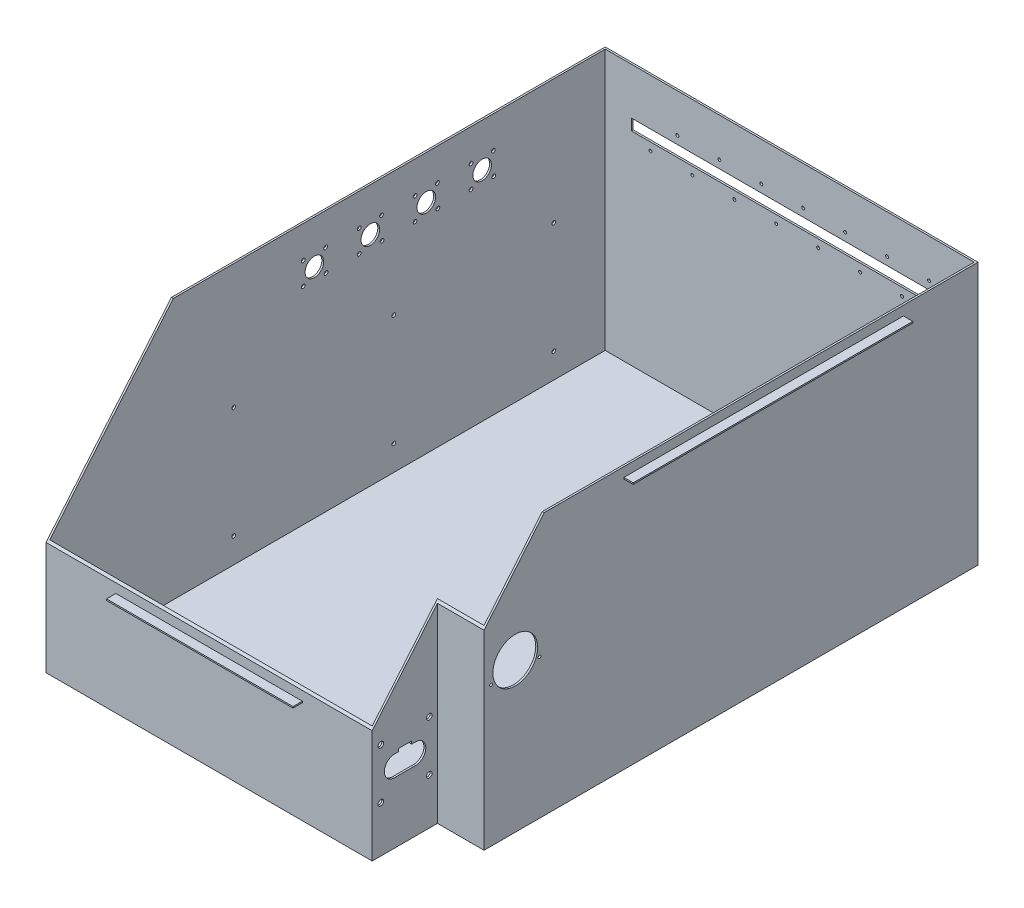
SolidWorks part; units mm, degrees
ref_plane "Front Plane" through (0, 0, 0) normal (0, 0, 1) x (1, 0, 0)
ref_plane "Top Plane" through (0, 0, 0) normal (0, 1, 0) x (1, 0, 0)
ref_plane "Right Plane" through (0, 0, 0) normal (1, 0, 0) x (0, 0, -1)
sketch "Sketch1" plane through (0, 0, 0) normal (0, 1, 0) x (1, 0, 0)
  line L1 (-200, 237.8263) -> (200, 237.8263)
  line L2 (-200, 237.8263) -> (-200, -362.1737)
  line L3 (-200, -362.1737) -> (150, -362.1737)
  line L4 (200, 237.8263) -> (200, -292.1737)
  line L6 (200, -292.1737) -> (150, -292.1737)
  line L7 (150, -292.1737) -> (150, -362.1737)
  line L8 (0, -55) -> (0, 55) construction
  point P1 (0, 237.8263)
  dimension "D1" = 600
  dimension "D2" = 400
  dimension "D5" = 70
  dimension "D6" = 50
extrude "Boss-Extrude1" add sketch "Sketch1" along normal blind 1.5
sketch "Sketch2" plane through (0, 1.5, 0) normal (0, 1, 0) x (1, 0, 0)
  line L60 (-198, 235.8263) -> (-198, -360.1737)
  line L61 (-198, -360.1737) -> (148, -360.1737)
  line L62 (148, -360.1737) -> (148, -290.1737)
  line L63 (148, -290.1737) -> (198, -290.1737)
  line L64 (198, -290.1737) -> (198, 235.8263)
  line L65 (198, 235.8263) -> (-198, 235.8263)
  line L66 (-200, 237.8263) -> (-200, -362.1737)
  line L67 (-200, -362.1737) -> (150, -362.1737)
  line L68 (150, -362.1737) -> (150, -292.1737)
  line L69 (150, -292.1737) -> (200, -292.1737)
  line L70 (200, -292.1737) -> (200, 237.8263)
  line L71 (200, 237.8263) -> (-200, 237.8263)
  line L72 (-200, 237.8263) -> (-200, -362.1737)
  line L73 (-200, -362.1737) -> (150, -362.1737)
  line L74 (150, -362.1737) -> (150, -292.1737)
  line L75 (150, -292.1737) -> (200, -292.1737)
  line L76 (200, -292.1737) -> (200, 237.8263)
  line L77 (200, 237.8263) -> (-200, 237.8263)
  dimension "D3" = 2
  dimension "D4" = 2
  dimension "D2" = 2
  dimension "D5" = 2
  dimension "D6" = 2
  dimension "D1" = 0
extrude "Boss-Extrude2" add sketch "Sketch2" along normal blind 280
sketch "Sketch3" plane through (-200, 0, 0) normal (-1, 0, 0) x (0, 0, 1)
  line L3 (362.1737, 281.5) -> (362.1737, 0) construction
  line L4 (362.1737, 121.1176) -> (227.5969, 281.5)
  line L6 (-237.8263, 281.5) -> (362.1737, 281.5) construction
  line L9 (362.1737, 281.5) -> (362.1737, 121.1176)
  line L10 (227.5969, 281.5) -> (362.1737, 281.5)
  dimension "D1" = 50
sketch "Sketch4" plane through (0, 0, -237.8263) normal (0, 0, -1) x (-1, 0, 0)
  line L0 (-200, 281.5) -> (-200, 0) construction
  line L1 (-200, 234.6761) -> (200, 234.6761)
  line L2 (-200, 234.6761) -> (-200, 192.2905)
  line L3 (-200, 192.2905) -> (200, 192.2905)
  line L4 (200, 234.6761) -> (200, 192.2905)
  line L5 (200, 281.5) -> (200, 0) construction
extrude "Boss-Extrude3" add sketch "Sketch4" against normal blind 2
extrude "Cut-Extrude1" cut sketch "Sketch3" against normal through all both and the other way through all
sketch "Sketch5" plane through (-200, 0, 0) normal (-1, 0, 0) x (0, 0, 1)
  line L0 (-115.8263, 223.1206) -> (-115.8263, 247.1206) construction
  line L5 (-115.8263, 223.1206) -> (-91.8263, 223.1206) construction
  line L6 (-115.8263, 247.1206) -> (-91.8263, 247.1206) construction
  line L7 (-91.8263, 223.1206) -> (-91.8263, 247.1206) construction
  line L8 (-115.8263, 223.1206) -> (-91.8263, 247.1206) construction
  line L9 (-115.8263, 247.1206) -> (-91.8263, 223.1206) construction
  line L10 (-55.8263, 223.1206) -> (-55.8263, 247.1206) construction
  line L11 (-55.8263, 223.1206) -> (-31.8263, 223.1206) construction
  line L12 (-55.8263, 247.1206) -> (-31.8263, 247.1206) construction
  line L13 (-31.8263, 223.1206) -> (-31.8263, 247.1206) construction
  line L14 (-55.8263, 223.1206) -> (-31.8263, 247.1206) construction
  line L15 (-55.8263, 247.1206) -> (-31.8263, 223.1206) construction
  line L16 (4.1737, 223.1206) -> (4.1737, 247.1206) construction
  line L17 (4.1737, 223.1206) -> (28.1737, 223.1206) construction
  line L18 (4.1737, 247.1206) -> (28.1737, 247.1206) construction
  line L19 (28.1737, 223.1206) -> (28.1737, 247.1206) construction
  line L20 (4.1737, 223.1206) -> (28.1737, 247.1206) construction
  line L21 (4.1737, 247.1206) -> (28.1737, 223.1206) construction
  line L22 (64.1737, 223.1206) -> (64.1737, 247.1206) construction
  line L23 (64.1737, 223.1206) -> (88.1737, 223.1206) construction
  line L24 (64.1737, 247.1206) -> (88.1737, 247.1206) construction
  line L25 (88.1737, 223.1206) -> (88.1737, 247.1206) construction
  line L26 (64.1737, 223.1206) -> (88.1737, 247.1206) construction
  line L27 (64.1737, 247.1206) -> (88.1737, 223.1206) construction
  line L28 (-235.8263, 281.5) -> (-235.8263, 1.5) construction
  circle A0 centre (-115.8263, 247.1206) radius 2
  circle A1 centre (-116.3263, 223.1259) radius 2
  circle A2 centre (-91.8263, 223.1206) radius 2
  circle A3 centre (-91.8263, 247.1206) radius 2
  circle A4 centre (-103.8263, 235.1206) radius 10
  circle A5 centre (-55.8263, 247.1206) radius 2
  circle A6 centre (-56.3263, 223.1259) radius 2
  circle A7 centre (-31.8263, 223.1206) radius 2
  circle A8 centre (-31.8263, 247.1206) radius 2
  circle A9 centre (-43.8263, 235.1206) radius 10
  circle A10 centre (4.1737, 247.1206) radius 2
  circle A11 centre (3.6737, 223.1259) radius 2
  circle A12 centre (28.1737, 223.1206) radius 2
  circle A13 centre (28.1737, 247.1206) radius 2
  circle A14 centre (16.1737, 235.1206) radius 10
  circle A15 centre (64.1737, 247.1206) radius 2
  circle A16 centre (63.6737, 223.1259) radius 2
  circle A17 centre (88.1737, 223.1206) radius 2
  circle A18 centre (88.1737, 247.1206) radius 2
  circle A19 centre (76.1737, 235.1206) radius 10
  point P9 (-103.8263, 235.1206)
  point P24 (-43.8263, 235.1206)
  point P38 (16.1737, 235.1206)
  point P52 (76.1737, 235.1206)
  dimension "D2" = 20
  dimension "D5" = 4
  dimension "D1" = 24
  dimension "D3" = 24
  dimension "D4" = 24
  dimension "D7" = 120
  dimension "D6" = 4
sketch "Sketch6" plane through (-198, 0, 0) normal (1, 0, 0) x (0, 0, -1)
  arc A0 (151.1392, 167.4539) -> (156.7272, 167.4539) centre (153.9332, 167.4539) ccw construction
  arc A1 (-68.8756, 167.4539) -> (-63.2876, 167.4539) centre (-66.0816, 167.4539) ccw construction
  arc A2 (-178.883, 167.4539) -> (-173.295, 167.4539) centre (-176.089, 167.4539) ccw construction
  arc A3 (151.1392, 167.4539) -> (156.7272, 167.4539) centre (153.9332, 167.4539) ccw
  arc A4 (-68.8756, 167.4539) -> (-63.2876, 167.4539) centre (-66.0816, 167.4539) ccw
  arc A5 (-178.883, 167.4539) -> (-173.295, 167.4539) centre (-176.089, 167.4539) ccw
  circle A6 centre (-176.089, 167.4539) radius 2.794
  circle A7 centre (-176.089, 167.4539) radius 4.5
  circle A8 centre (-64.4633, 167.4539) radius 4.5
  circle A9 centre (-64.4633, 167.4539) radius 2.794
  circle A10 centre (155.5515, 167.4539) radius 2.794
  circle A11 centre (155.5515, 167.4539) radius 4.5
  dimension "D1" = 9
extrude "Boss-Extrude4" [suppressed] add sketch "Sketch6" along normal blind 50 contours A4 A9 | A8 | A7 | A6 | A11 | A10
sketch "Sketch8" plane through (-198, 0, 0) normal (1, 0, 0) x (0, 0, -1)
  line L0 (235.8263, 1.5) -> (-360.1737, 1.5) construction
  line L1 (-360.1737, 123.5011) -> (-360.1737, 1.5) construction
  circle A0 centre (-265.6737, 172.1992) radius 2.39
  circle A1 centre (-265.6737, 172.1992) radius 4.39
  circle A2 centre (-265.1737, 16.5) radius 2.39
  circle A3 centre (-265.1737, 16.5) radius 4.39
  dimension "D3" = 4.78
  dimension "D4" = 2
  dimension "D1" = 155.7
  dimension "D2" = 15
  dimension "D5" = 95
extrude "Boss-Extrude5" [suppressed] add sketch "Sketch8" along normal blind 15
sketch "Sketch10" plane through (148, 0, 0) normal (-1, 0, 0) x (0, 0, 1)
  line L0 (315.6737, 86.5) -> (320.9237, 86.5) construction
  line L1 (315.6737, 66.5) -> (338.1737, 66.5) construction
  line L2 (338.1737, 76.5) -> (315.6737, 76.5) construction
  line L3 (360.1737, 1.5) -> (290.1737, 1.5) construction
  line L5 (320.9237, 86.5) -> (320.9237, 89.5) construction
  line L6 (320.9237, 89.5) -> (332.9237, 89.5) construction
  line L7 (332.9237, 86.5) -> (332.9237, 89.5) construction
  line L8 (360.1737, 123.5011) -> (360.1737, 1.5) construction
  line L9 (332.9237, 86.5) -> (338.1737, 86.5) construction
  line L10 (319.9237, 90.5) -> (333.9237, 90.5)
  line L11 (333.9237, 87.5) -> (333.9237, 90.5)
  line L12 (333.9237, 87.5) -> (338.1737, 87.5)
  line L13 (315.6737, 65.5) -> (338.1737, 65.5)
  line L14 (315.6737, 87.5) -> (319.9237, 87.5)
  line L15 (319.9237, 87.5) -> (319.9237, 90.5)
  line L17 (300.9737, 49.55) -> (352.8737, 49.55) construction
  line L18 (300.9737, 49.55) -> (300.9737, 103.45) construction
  line L19 (300.9737, 103.45) -> (352.8737, 103.45) construction
  line L20 (352.8737, 49.55) -> (352.8737, 103.45) construction
  line L21 (300.9737, 49.55) -> (352.8737, 103.45) construction
  line L22 (300.9737, 103.45) -> (352.8737, 49.55) construction
  arc A0 (315.6737, 86.5) -> (315.6737, 66.5) centre (315.6737, 76.5) ccw construction
  arc A1 (338.1737, 66.5) -> (338.1737, 86.5) centre (338.1737, 76.5) ccw construction
  arc A2 (338.1737, 65.5) -> (338.1737, 87.5) centre (338.1737, 76.5) ccw
  arc A3 (315.6737, 87.5) -> (315.6737, 65.5) centre (315.6737, 76.5) ccw
  circle A4 centre (300.9737, 103.45) radius 3
  circle A5 centre (352.8737, 103.45) radius 3
  circle A6 centre (300.9737, 49.55) radius 3
  circle A7 centre (352.8737, 49.55) radius 3
  point P12 (326.9237, 89.5)
  point P13 (326.9237, 76.5)
  point P26 (326.9237, 76.5)
  dimension "D1" = 65
  dimension "D2" = 22.5
  dimension "D6" = 20
  dimension "D10" = 6
  dimension "D3" = 22
  dimension "D4" = 12
  dimension "D5" = 3
  dimension "D8" = 51.9
  dimension "D9" = 53.9
  dimension "D7" = 1
extrude "Cut-Extrude2" cut sketch "Sketch10" against normal up to surface (2 mm away)
sketch "Sketch11" plane through (148, 0, 0) normal (-1, 0, 0) x (0, 0, 1)
  line L0 (298.4737, 103.43) -> (298.4737, 49.53) construction
  line L13 (315.6737, 66.5) -> (338.1737, 66.5) construction
  line L14 (315.6737, 86.5) -> (320.9237, 86.5) construction
  line L15 (315.6737, 66.5) -> (338.1737, 66.5)
  line L19 (315.6737, 86.5) -> (318.4237, 86.5)
  line L20 (333.9237, 90.5) -> (319.9237, 90.5)
  line L21 (333.9237, 90.5) -> (319.9237, 90.5)
  line L22 (333.9237, 87.5) -> (333.9237, 90.5)
  line L23 (333.9237, 87.5) -> (333.9237, 90.5)
  line L28 (330.4237, 86.5) -> (320.9237, 86.5)
  line L29 (315.7815, 66) -> (338.2021, 66)
  line L30 (330.9237, 86) -> (320.2852, 86)
  line L31 (330.9237, 86) -> (330.9237, 91)
  line L32 (330.9237, 91) -> (317.9237, 91)
  line L33 (317.9237, 91) -> (317.9237, 87)
  line L34 (315.7815, 87) -> (317.9237, 87)
  line L36 (298.4737, 103.43) -> (350.3737, 103.43) construction
  line L43 (333.9237, 90.5) -> (319.9237, 90.5)
  line L44 (333.9237, 90.5) -> (319.9237, 90.5)
  line L45 (333.9237, 87.5) -> (333.9237, 90.5)
  line L46 (333.9237, 87.5) -> (333.9237, 90.5)
  line L47 (338.1737, 87.5) -> (333.9237, 87.5)
  line L48 (338.1737, 87.5) -> (333.9237, 87.5)
  line L49 (315.6737, 65.5) -> (338.1737, 65.5)
  line L50 (315.6737, 65.5) -> (338.1737, 65.5)
  line L51 (319.9237, 87.5) -> (315.6737, 87.5)
  line L52 (319.9237, 87.5) -> (315.6737, 87.5)
  line L53 (319.9237, 90.5) -> (319.9237, 87.5)
  line L54 (319.9237, 90.5) -> (319.9237, 87.5)
  line L55 (333.9237, 90.5) -> (319.9237, 90.5)
  line L56 (333.9237, 90.5) -> (319.9237, 90.5)
  line L57 (333.9237, 87.5) -> (333.9237, 90.5)
  line L58 (333.9237, 87.5) -> (333.9237, 90.5)
  line L59 (338.1737, 87.5) -> (333.9237, 87.5)
  line L60 (338.1737, 87.5) -> (333.9237, 87.5)
  line L61 (315.6737, 65.5) -> (338.1737, 65.5)
  line L62 (315.6737, 65.5) -> (338.1737, 65.5)
  line L63 (319.9237, 87.5) -> (315.6737, 87.5)
  line L64 (319.9237, 87.5) -> (315.6737, 87.5)
  line L65 (319.9237, 90.5) -> (319.9237, 87.5)
  line L66 (319.9237, 90.5) -> (319.9237, 87.5)
  line L67 (330.4237, 86.5) -> (330.4237, 90.5) construction
  line L68 (330.4237, 90.5) -> (318.4237, 90.5) construction
  line L69 (318.4237, 90.5) -> (318.4237, 86.5) construction
  line L70 (338.1737, 87.5) -> (333.9237, 87.5)
  line L71 (338.1737, 87.5) -> (333.9237, 87.5)
  line L72 (315.6737, 65.5) -> (338.1737, 65.5)
  line L73 (315.6737, 65.5) -> (338.1737, 65.5)
  line L74 (319.9237, 87.5) -> (315.6737, 87.5)
  line L75 (319.9237, 87.5) -> (315.6737, 87.5)
  line L76 (319.9237, 90.5) -> (319.9237, 87.5)
  line L77 (319.9237, 90.5) -> (319.9237, 87.5)
  arc A4 (338.2021, 66) -> (320.2852, 86) centre (336.3485, 82.3648) ccw
  arc A5 (338.1737, 65.5) -> (338.1737, 87.5) centre (338.1737, 76.5) ccw
  arc A7 (338.1737, 65.5) -> (338.1737, 87.5) centre (338.1737, 76.5) ccw
  arc A9 (315.7815, 87) -> (315.7815, 66) centre (311.0911, 76.5) ccw
  circle A10 centre (298.4737, 103.43) radius 3
  circle A11 centre (298.4737, 49.53) radius 3
  circle A12 centre (350.3737, 103.43) radius 3
  circle A13 centre (350.3737, 49.53) radius 3
  arc A16 (338.1737, 66.5) -> (320.9237, 86.5) centre (336.3485, 82.3648) ccw construction
  arc A17 (338.1737, 65.5) -> (338.1737, 87.5) centre (338.1737, 76.5) ccw
  arc A18 (315.6737, 87.5) -> (315.6737, 65.5) centre (315.6737, 76.5) ccw
  arc A19 (315.6737, 87.5) -> (315.6737, 65.5) centre (315.6737, 76.5) ccw
  arc A20 (315.6737, 86.5) -> (315.6737, 66.5) centre (311.0911, 76.5) ccw construction
  arc A21 (338.1737, 65.5) -> (338.1737, 87.5) centre (338.1737, 76.5) ccw
  arc A22 (315.6737, 87.5) -> (315.6737, 65.5) centre (315.6737, 76.5) ccw
  arc A23 (315.6737, 87.5) -> (315.6737, 65.5) centre (315.6737, 76.5) ccw
  arc A24 (338.1737, 65.5) -> (338.1737, 87.5) centre (338.1737, 76.5) ccw
  arc A25 (338.1737, 65.5) -> (338.1737, 87.5) centre (338.1737, 76.5) ccw
  arc A26 (315.6737, 87.5) -> (315.6737, 65.5) centre (315.6737, 76.5) ccw
  arc A27 (315.6737, 87.5) -> (315.6737, 65.5) centre (315.6737, 76.5) ccw
  dimension "D5" = 6
  dimension "D6" = 51.9
  dimension "D7" = 53.9
  dimension "D1" = 0
  dimension "D2" = 0
  dimension "D3" = 0
  dimension "D4" = 0.5
extrude "Cut-Extrude3" [suppressed] cut sketch "Sketch11" against normal through all
sketch "Sketch14" plane through (148, 0, 0) normal (-1, 0, 0) x (0, 0, 1)
  line L0 (362.1737, 121.1176) -> (362.1737, 0) construction
  line L1 (362.1737, 0) -> (292.1737, 0) construction
  circle A0 centre (297.2737, 103.43) radius 3
  circle A1 centre (349.1737, 103.43) radius 3
  circle A2 centre (349.1737, 49.53) radius 3
  circle A3 centre (297.2737, 49.53) radius 3
  dimension "D5" = 6
  dimension "D1" = 51.9
  dimension "D2" = 53.9
  dimension "D3" = 13
  dimension "D4" = 103.43
extrude "Cut-Extrude4" [suppressed] cut sketch "Sketch14" against normal up to surface (1.5 mm away)
sketch "Sketch15" plane through (198, 0, 0) normal (-1, 0, 0) x (0, 0, 1)
  line L1 (-223.8263, 252.1363) -> (-208.8263, 252.1363)
  line L2 (-223.8263, 252.1363) -> (-223.8263, 250.6363)
  line L3 (-223.8263, 250.6363) -> (-208.8263, 250.6363)
  line L4 (-208.8263, 252.1363) -> (-208.8263, 250.6363)
  line L5 (-235.8263, 281.5) -> (-235.8263, 1.5) construction
  line L6 (196.1737, 252.1363) -> (211.1737, 252.1363)
  line L7 (196.1737, 250.6363) -> (211.1737, 250.6363)
  line L8 (196.1737, 252.1363) -> (196.1737, 250.6363)
  line L9 (211.1737, 252.1363) -> (211.1737, 250.6363)
  dimension "D1" = 1.5
  dimension "D2" = 15
  dimension "D3" = 12
  dimension "D4" = 432
  dimension "D5" = 15
extrude "Boss-Extrude6" [suppressed] add sketch "Sketch15" along normal blind 15
ref_plane "Plane1" [suppressed] through (0, 0, -203.8263) normal (0, 0, -1) x (-1, 0, 0)
sketch "Sketch17" [suppressed] plane through (0, 0, -208.8263) normal (0, 0, 1) x (1, 0, 0)
  line L0 (198, 250.6363) -> (198, 235.6363)
  line L1 (198, 281.5) -> (198, 207.307) construction
  line L2 (198, 235.6363) -> (183, 250.6363)
  line L3 (183, 250.6363) -> (198, 250.6363)
  dimension "D1" = 15
extrude "Boss-Extrude7" [suppressed] add sketch "Sketch17" against normal blind 1.5
ref_plane "Plane2" [suppressed] through (0, 0, 191.1737) normal (0, 0, 1) x (1, 0, 0)
sketch "Sketch18" [suppressed] plane through (0, 0, 196.1737) normal (0, 0, 1) x (1, 0, 0)
  line L0 (198, 250.6363) -> (198, 235.6363)
  line L1 (198, 281.5) -> (198, 207.307) construction
  line L2 (198, 235.6363) -> (183, 250.6363)
  line L3 (183, 250.6363) -> (198, 250.6363)
  dimension "D1" = 15
extrude "Boss-Extrude8" [suppressed] add sketch "Sketch18" along normal blind 1.5
sketch "Sketch20" [suppressed] plane through (0, 252.1363, 0) normal (0, 1, 0) x (1, 0, 0)
  line L1 (183, 223.8263) -> (198, 223.8263) construction
  line L2 (183, 208.8263) -> (183, 223.8263) construction
  line L3 (183, -211.1737) -> (198, -211.1737) construction
  line L4 (183, -211.1737) -> (183, -196.1737) construction
  circle A0 centre (190.5, 216.3263) radius 2.4159
  circle A1 centre (190.5, -203.6737) radius 2
  dimension "D3" = 4
  dimension "D1" = 7.5
  dimension "D2" = 7.5
  dimension "D4" = 7.5
  dimension "D5" = 7.5
extrude "Cut-Extrude5" [suppressed] cut sketch "Sketch20" against normal up to surface (1.5 mm away)
extrude "Cut-Extrude7" cut sketch "Sketch5" against normal up to surface (2 mm away) up to face at (-198, 137.9002, 95.2583)
sketch "Sketch21" plane through (0, 0, -237.8263) normal (0, 0, -1) x (-1, 0, 0)
  line L0 (-200, 281.5) -> (200, 281.5) construction
  line L1 (-150, 271.5) -> (150, 271.5)
  line L2 (-150, 271.5) -> (-150, 270)
  line L3 (-150, 270) -> (150, 270)
  line L4 (150, 271.5) -> (150, 270)
  point P6 (0, 281.5)
  point P7 (0, 271.5)
  dimension "D1" = 1.5
  dimension "D2" = 300
  dimension "D3" = 10
extrude "Boss-Extrude9" add sketch "Sketch21" along normal blind 10
sketch "Sketch22" plane through (-200, 0, 0) normal (-1, 0, 0) x (0, 0, 1)
  line L0 (-237.8263, 281.5) -> (227.5969, 281.5) construction
  line L1 (-157.8263, 271.5) -> (142.1737, 271.5)
  line L2 (-157.8263, 271.5) -> (-157.8263, 270)
  line L3 (-157.8263, 270) -> (142.1737, 270)
  line L4 (142.1737, 271.5) -> (142.1737, 270)
  line L5 (-237.8263, 281.5) -> (-237.8263, 0) construction
  dimension "D1" = 1.5
  dimension "D2" = 10
  dimension "D3" = 80
  dimension "D4" = 300
extrude "Boss-Extrude10" add sketch "Sketch22" along normal blind 10
ref_plane "Plane3" through (0, 0, -77.8263) normal (0, 0, -1) x (-1, 0, 0)
sketch "Sketch23" plane through (0, 0, -77.8263) normal (0, 0, -1) x (-1, 0, 0)
  line L0 (210, 270) -> (200, 270) construction
  line L1 (210, 270) -> (200, 270)
  line L2 (210, 270) -> (200, 260)
  line L3 (200, 281.5) -> (200, 0) construction
  line L4 (200, 260) -> (200, 270)
  dimension "D1" = 10
extrude "Boss-Extrude11" add sketch "Sketch23" along normal mid plane 1.5
ref_plane "Plane4" through (0, 0, 52.1737) normal (0, 0, 1) x (1, 0, 0)
sketch "Sketch24" plane through (0, 0, 52.1737) normal (0, 0, 1) x (1, 0, 0)
  line L6 (-210, 270) -> (-200, 260)
  line L7 (-200, 260) -> (-200, 270)
  line L8 (-200, 270) -> (-210, 270)
  line L9 (-210, 270) -> (-200, 260)
  line L10 (-200, 260) -> (-200, 270)
  line L11 (-200, 270) -> (-210, 270)
  dimension "D1" = 0
extrude "Boss-Extrude12" add sketch "Sketch24" along normal mid plane 1.5
ref_plane "Plane5" through (100, 0, 0) normal (1, 0, 0) x (0, 0, -1)
sketch "Sketch25" plane through (100, 0, 0) normal (1, 0, 0) x (0, 0, -1)
  line L0 (247.8263, 270) -> (237.8263, 270)
  line L1 (237.8263, 270) -> (237.8263, 260)
  line L2 (237.8263, 281.5) -> (237.8263, 0) construction
  line L3 (237.8263, 260) -> (247.8263, 270)
  dimension "D1" = 10
extrude "Boss-Extrude13" add sketch "Sketch25" along normal mid plane 1.5
ref_plane "Plane6" through (-100, 0, 0) normal (-1, 0, 0) x (0, 0, 1)
sketch "Sketch26" plane through (-100, 0, 0) normal (-1, 0, 0) x (0, 0, 1)
  line L3 (-247.8263, 270) -> (-237.8263, 260)
  line L4 (-237.8263, 260) -> (-237.8263, 270)
  line L5 (-237.8263, 270) -> (-247.8263, 270)
  line L6 (-247.8263, 270) -> (-237.8263, 260)
  line L7 (-237.8263, 260) -> (-237.8263, 270)
  line L8 (-237.8263, 270) -> (-247.8263, 270)
  dimension "D1" = 0
extrude "Boss-Extrude14" add sketch "Sketch26" along normal mid plane 1.5
mirror "Mirror1" about plane through (0, 0, 0) normal (1, 0, 0) of "Boss-Extrude11", "Boss-Extrude12", "Boss-Extrude10"
sketch "Sketch27" plane through (0, 0, 362.1737) normal (0, 0, 1) x (1, 0, 0)
  line L0 (150, 121.1176) -> (-200, 121.1176) construction
  line L1 (-125, 111.1176) -> (75, 111.1176)
  line L2 (-125, 111.1176) -> (-125, 109.6176)
  line L3 (-125, 109.6176) -> (75, 109.6176)
  line L4 (75, 111.1176) -> (75, 109.6176)
  line L5 (150, 121.1176) -> (-200, 121.1176) construction
  point P6 (-25, 121.1176)
  point P7 (-25, 111.1176)
  dimension "D1" = 1.5
  dimension "D2" = 200
  dimension "D3" = 10
extrude "Boss-Extrude15" add sketch "Sketch27" along normal blind 10
ref_plane "Plane7" through (-95, 0, 0) normal (-1, 0, 0) x (0, 0, 1)
sketch "Sketch28" plane through (-95, 0, 0) normal (-1, 0, 0) x (0, 0, 1)
  line L0 (372.1737, 109.6176) -> (362.1737, 109.6176)
  line L1 (362.1737, 109.6176) -> (362.1737, 99.6176)
  line L2 (362.1737, 121.1176) -> (362.1737, 0) construction
  line L3 (362.1737, 99.6176) -> (372.1737, 109.6176)
  dimension "D1" = 10
extrude "Boss-Extrude16" add sketch "Sketch28" along normal mid plane 1.5
ref_plane "Plane8" through (45, 0, 0) normal (1, 0, 0) x (0, 0, -1)
sketch "Sketch29" plane through (45, 0, 0) normal (1, 0, 0) x (0, 0, -1)
  line L3 (-372.1737, 109.6176) -> (-362.1737, 99.6176)
  line L4 (-362.1737, 99.6176) -> (-362.1737, 109.6176)
  line L5 (-362.1737, 109.6176) -> (-372.1737, 109.6176)
  line L6 (-372.1737, 109.6176) -> (-362.1737, 99.6176)
  line L7 (-362.1737, 99.6176) -> (-362.1737, 109.6176)
  line L8 (-362.1737, 109.6176) -> (-372.1737, 109.6176)
  dimension "D1" = 0
extrude "Boss-Extrude17" add sketch "Sketch29" along normal mid plane 1.5
sketch "Sketch30" plane through (200, 0, 0) normal (1, 0, 0) x (0, 0, -1)
  line L1 (-292.1737, 0) -> (237.8263, 0) construction
  line L2 (-292.1737, 204.5403) -> (-292.1737, 0) construction
  circle A0 centre (-258.6737, 160) radius 24
  circle A1 centre (-284.6737, 150) radius 1.5
  circle A2 centre (-232.6737, 150) radius 1.5
  dimension "D1" = 48
  dimension "D2" = 3
  dimension "D3" = 3
  dimension "D4" = 26
  dimension "D5" = 10
  dimension "D6" = 26
  dimension "D7" = 10
  dimension "D8" = 160
  dimension "D9" = 33.5
extrude "Cut-Extrude8" cut sketch "Sketch30" against normal up to surface (2 mm away) up to face at (198, 154.5848, 67.2583)
sketch "Sketch33" plane through (-200, 0, 0) normal (-1, 0, 0) x (0, 0, 1)
  line L0 (-237.8263, 281.5) -> (-237.8263, 0) construction
  line L1 (-237.8263, 0) -> (362.1737, 0) construction
  circle A0 centre (-180.6263, 147.77) radius 2
  circle A1 centre (-180.6263, 28.39) radius 2
  circle A2 centre (-8.9263, 147.77) radius 2
  circle A3 centre (-8.9263, 28.39) radius 2
  circle A4 centre (162.7737, 147.77) radius 2
  circle A5 centre (162.7737, 28.39) radius 2
  dimension "D3" = 4
  dimension "D1" = 57.2
  dimension "D2" = 119.38
  dimension "D4" = 28.39
  dimension "D5" = 3
extrude "Cut-Extrude9" cut sketch "Sketch33" against normal up to surface (2 mm away) up to face at (-198, 223.1206, 26.1737)
sketch "Sketch42" plane through (0, 0, -235.8263) normal (0, 0, 1) x (1, 0, 0)
  line L8 (200, 281.5) -> (-200, 281.5) construction
  line L9 (170, 219.5) -> (-170, 219.5)
  line L10 (170, 219.5) -> (170, 231.5)
  line L11 (170, 231.5) -> (-170, 231.5)
  line L12 (-170, 219.5) -> (-170, 231.5)
  line L15 (200, 225.5) -> (-200, 225.5) construction
  line L16 (200, 281.5) -> (200, 0) construction
  line L17 (-200, 281.5) -> (-200, 0) construction
  line L18 (-72.5, 243) -> (-107.5, 243)
  line L19 (-117.5, 208) -> (-152.5, 208) construction
  line L20 (-117.5, 208) -> (-117.5, 243) construction
  line L21 (-117.5, 243) -> (-152.5, 243) construction
  line L22 (-152.5, 208) -> (-152.5, 243) construction
  line L25 (-72.5, 208) -> (-72.5, 243)
  line L26 (-107.5, 208) -> (-107.5, 243)
  line L27 (-72.5, 208) -> (-107.5, 208)
  line L29 (-27.5, 243) -> (-62.5, 243)
  line L30 (-27.5, 208) -> (-27.5, 243)
  line L31 (-62.5, 208) -> (-62.5, 243)
  line L32 (-27.5, 208) -> (-62.5, 208)
  line L34 (17.5, 243) -> (-17.5, 243)
  line L35 (17.5, 208) -> (17.5, 243)
  line L36 (-17.5, 208) -> (-17.5, 243)
  line L37 (17.5, 208) -> (-17.5, 208)
  line L39 (62.5, 243) -> (27.5, 243)
  line L40 (62.5, 208) -> (62.5, 243)
  line L41 (27.5, 208) -> (27.5, 243)
  line L42 (62.5, 208) -> (27.5, 208)
  line L44 (107.5, 243) -> (72.5, 243)
  line L45 (107.5, 208) -> (107.5, 243)
  line L46 (72.5, 208) -> (72.5, 243)
  line L47 (107.5, 208) -> (72.5, 208)
  line L49 (152.5, 243) -> (117.5, 243)
  line L50 (152.5, 208) -> (152.5, 243)
  line L51 (117.5, 208) -> (117.5, 243)
  line L52 (152.5, 208) -> (117.5, 208)
  circle A0 centre (-120.5, 240) radius 1.6
  circle A1 centre (-149.5, 211) radius 1.6
  circle A2 centre (-75.5, 240) radius 1.6
  circle A3 centre (-104.5, 211) radius 1.6
  circle A4 centre (-30.5, 240) radius 1.6
  circle A5 centre (-59.5, 211) radius 1.6
  circle A6 centre (14.5, 240) radius 1.6
  circle A7 centre (-14.5, 211) radius 1.6
  circle A8 centre (59.5, 240) radius 1.6
  circle A9 centre (30.5, 211) radius 1.6
  circle A10 centre (104.5, 240) radius 1.6
  circle A11 centre (75.5, 211) radius 1.6
  circle A12 centre (149.5, 240) radius 1.6
  circle A13 centre (120.5, 211) radius 1.6
  point P0 (0, 225.5)
  point P13 (-135, 225.5)
  dimension "D4" = 3
  dimension "D6" = 3
  dimension "D1" = 50
  dimension "D2" = 17.5
  dimension "D5" = 3
  dimension "D7" = 3
  dimension "D3" = 7
extrude "Cut-Extrude13" cut sketch "Sketch42" against normal blind 40
sketch "Sketch43" plane through (0, 0, 0) normal (0, -1, 0) x (1, 0, 0)
  line L0 (-200, 362.1737) -> (150, 362.1737) construction
  line L1 (150, 292.1737) -> (200, 292.1737)
  line L2 (150, 292.1737) -> (150, 362.1737)
  line L3 (150, 362.1737) -> (200, 362.1737)
  line L4 (200, 292.1737) -> (200, 362.1737)
  line L5 (200, 292.1737) -> (200, -237.8263) construction
